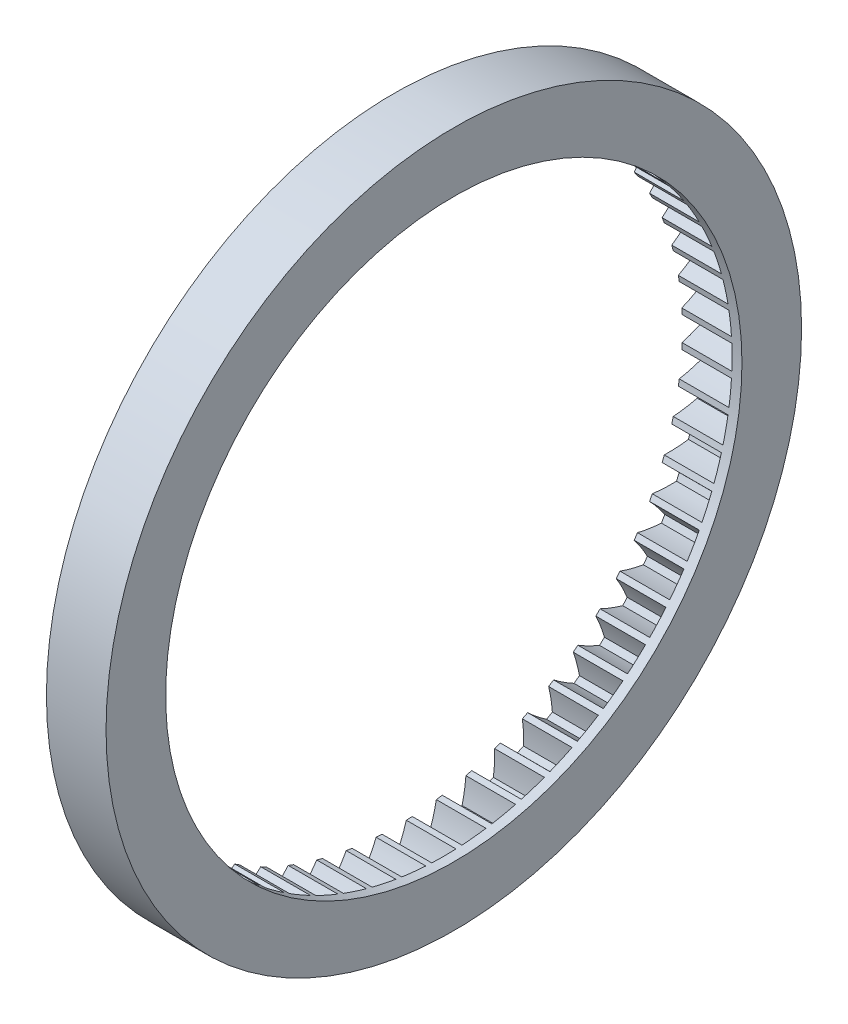
SolidWorks part; units mm, degrees
ref_plane "Plane1" through (0, 0, 0) normal (0, 0, 1) x (1, 0, 0)
ref_plane "Plane2" through (0, 0, 0) normal (0, 1, 0) x (1, 0, 0)
ref_plane "Plane3" through (0, 0, 0) normal (1, 0, 0) x (0, 0, -1)
sketch "HoldingSke" plane through (0, 0, 0) normal (0, 1, 0) x (1, 0, 0)
  line L0 (0, 0) -> (0.5, -0.866)
  line L1 (-15, 0) -> (100, 0) construction
  line L2 (0, 0) -> (-2.1039, 2.3779)
  line L3 (0, 0) -> (-11.863, 4.5341)
  line L4 (0, 0) -> (4.318, 7.479)
  line L5 (0, 0) -> (-23.7986, -8.8762)
  line L6 (0, 0) -> (-10.5278, -7.1032)
  line L7 (-2.1039, 2.3779) -> (3.3635, 27.1825)
  line L8 (-76.2, 3.3779) -> (-54.61, 3.3779)
  line L9 (-71.009, 38.7566) -> (-53.1078, 45.2721)
  line L10 (-76.2, 71.12) -> (104.1128, 71.12)
  line L11 (0, 0) -> (-5, 0)
  line L12 (-76.2, 101.6) -> (-76.162, 101.6)
  line L13 (24.9733, 27.94) -> (52.9518, 28.4284)
  line L14 (24.9733, 27.94) -> (24.9743, 27.94)
  line L15 (24.9733, 27.94) -> (100.4006, 29.5858)
  circle A0 centre (0, 0) radius 35
  circle A1 centre (0, 0) radius 12.7
  circle A2 centre (0, 0) radius 12.7
  dimension "MHD" = 25.4
  dimension "Hub_dia" = 25.4
  dimension "Diameter" = 70
  dimension "Num_teeth" = 60
  dimension "Pitch" = 1
  dimension "Overall_len" = 25.4
  dimension "Show_teeth" = 60
  dimension "Thickness" = 12.7
  dimension "OAL" = 25.4001
  dimension "T_dim" = 21.59
  dimension "Ap" = 20
  dimension "H" = 19.05
  dimension "Pitch_radius" = 180.3128
  dimension "Backlash" = 0.038
  dimension "Addendum_fac" = 1
  dimension "Dedendum_fac" = 1.25
  dimension "Clearance_fac" = 0.25
  dimension "Dedendum_add" = 0.001
  dimension "Module" = 1
sketch "BasProSke" plane through (0, 0, 0) normal (0, 1, 0) x (1, 0, 0)
  line L0 (-10, 0) -> (60, 0) construction
  line L1 (0, 29) -> (0, 35)
  line L2 (0, 29) -> (5, 29)
  line L3 (5, 29) -> (5, 35)
  line L4 (5, 35) -> (0, 35)
  dimension "Diameter" = 70
  dimension "Inside_diameter" = 58
revolve "Base-Revolve" add sketch "BasProSke" angle 360 about L0
sketch "TooCutSke" plane through (0, 0, 0) normal (1, 0, 0) x (0, 0, -1)
  line L3 (0.8803, 29.9871) -> (0.8803, 53.6633) construction
  line L4 (0, 0) -> (0, 59.563) construction
  line L5 (0, 0) -> (-3.576, 68.2339) construction
  line L6 (-13.1633, 24.7167) -> (36.4631, 27.3175) construction
  circle A0 centre (0, 0) radius 30 construction
  circle A1 centre (0, 0) radius 31.251 construction
  circle A2 centre (0, 0) radius 25.3717 construction
  circle A3 centre (0, 0) radius 28.9746 construction
  arc A4 (1.2274, 28.9486) -> (0.3395, 31.2492) centre (-13.1633, 24.7167) ccw
  arc A5 (1.2274, 28.9486) -> (-1.2274, 28.9486) centre (0, 0) ccw
  arc A6 (0.3395, 31.2492) -> (-0.3395, 31.2492) centre (0, 0) ccw
  arc A7 (-0.3395, 31.2492) -> (-1.2274, 28.9486) centre (13.1633, 24.7167) ccw
  dimension "Pitch_dia" = 60
  dimension "Base_dia" = 50.7434
  dimension "Root_dia" = 62.502
  dimension "Overcut_dia" = 57.9492
  dimension "Flank_rad" = 15
  dimension "Half_ang" = 3
  dimension "Half_CT" = 0.8803
extrude "ToothCut" cut sketch "TooCutSke" along normal through all
fillet "Breaks" [suppressed] radius 0.1
fillet "RootFillets" [suppressed] radius 0.251
pattern_circular "TeethCuts" count 60 every 6 about axis through (-10, 0, 0) along (1, 0, 0) of "RootFillets", "Breaks", "ToothCut"
sketch "Croquis1" plane through (5, 0, 0) normal (1, 0, 0) x (0, 0, -1)
  circle A0 centre (0, 0) radius 35
  circle A1 centre (0, 0) radius 29
extrude "Saliente-Extruir1" add sketch "Croquis1" along normal blind 1
equation "' \"Module@HoldingSke\" = 6.35"
equation "' \"Num_teeth@HoldingSke\" = 24"
equation "' \"Ap@HoldingSke\" =  14.5"
equation "' \"Ap@HoldingSke\" = 14.5"
equation "' \"Width@HoldingSke\" = 12"
equation "' \"Diameter@HoldingSke\" = 8 * 25.4"
equation "' \"Show_teeth@HoldingSke\" = 100"
equation "' \"Backlash@HoldingSke\" = 0.009 * 25.4"
equation "' \"Addendum_fac@HoldingSke\" = 1.0"
equation "' \"Dedendum_fac@HoldingSke\" = 1.25"
equation "' \"Dedendum_add@HoldingSke\" = 0.00005 * 25.4"
equation "' \"Clearance_fac@HoldingSke\" = 0.25"
equation "\"Pitch@HoldingSke\" = 1 / \"Module@HoldingSke\" "
equation "\"Overcut_dia@TooCutSke\" = (\"Num_teeth@HoldingSke\" - 2 * \"Addendum_fac@HoldingSke\") / \"Pitch@HoldingSke\" - 0.002 * 25.4"
equation "\"Pitch_dia@TooCutSke\" = \"Num_teeth@HoldingSke\" / \"Pitch@HoldingSke\""
equation "\"Base_dia@TooCutSke\" = \"Num_teeth@HoldingSke\" / \"Pitch@HoldingSke\" * cos((\"Ap@HoldingSke\"  * 3.14159265 / 180)) * 0.90"
equation "\"Root_dia@TooCutSke\" = \"Num_teeth@HoldingSke\"  / \"Pitch@HoldingSke\" + 2 *  \"Dedendum_fac@HoldingSke\"/ \"Pitch@HoldingSke\" + \"Dedendum_add@HoldingSke\" * 2"
equation "\"Half_ang@TooCutSke\" = 180 / \"Num_teeth@HoldingSke\""
equation "\"Half_CT@TooCutSke\" = \"Num_teeth@HoldingSke\" / \"Pitch@HoldingSke\" * sin((3.14159265 / 2 / \"Num_teeth@HoldingSke\")) / 2 + 10 * \"Backlash@HoldingSke\" / 4"
equation "\"Flank_rad@TooCutSke\" = \"Num_teeth@HoldingSke\" / \"Pitch@HoldingSke\" / 4"
equation "\"Radius@RootFillets\"= \"Clearance_fac@HoldingSke\" / \"Pitch@HoldingSke\" + \"Dedendum_add@HoldingSke\""
equation "\"Break_rad@Breaks\" = 0.02 / \"Pitch@HoldingSke\" * 5"
equation "\"Num_teeth@TeethCuts\" = int( \"Show_teeth@HoldingSke\" ) + 1"
equation "\"Num_teeth@TeethCuts\" = ((sgn( \"Num_teeth@TeethCuts\" - \"Num_teeth@HoldingSke\" )-1)*( \"Num_teeth@TeethCuts\" - \"Num_teeth@HoldingSke\" ))/-2+ \"Num_teeth@HoldingSke\""
equation "\"Num_teeth@TeethCuts\" = ((sgn( \"Num_teeth@TeethCuts\" - 2.0)+1)*( \"Num_teeth@TeethCuts\" - 2.0))/2 +2.0"
equation "\"Angle@TeethCuts\" = 360.0 / \"Num_teeth@HoldingSke\""
equation "\"Diameter@BasProSke\" = \"Num_teeth@HoldingSke\"  / \"Pitch@HoldingSke\" + 2 *  \"Dedendum_fac@HoldingSke\"/ \"Pitch@HoldingSke\" + \"Dedendum_add@HoldingSke\" * 2 + 0.002 * 25.4"
equation "\"Diameter@BasProSke\" = ((sgn( \"Diameter@BasProSke\"  - \"Diameter@HoldingSke\" )+1)*( \"Diameter@BasProSke\"  - \"Diameter@HoldingSke\" ))/2 + \"Diameter@HoldingSke\""
equation "\"Inside_diameter@BasProSke\" =  (\"Num_teeth@HoldingSke\" - 2 * \"Addendum_fac@HoldingSke\") / \"Pitch@HoldingSke\" "
equation "\"Thickness@BasProSke\"  = \"Width@HoldingSke\""
